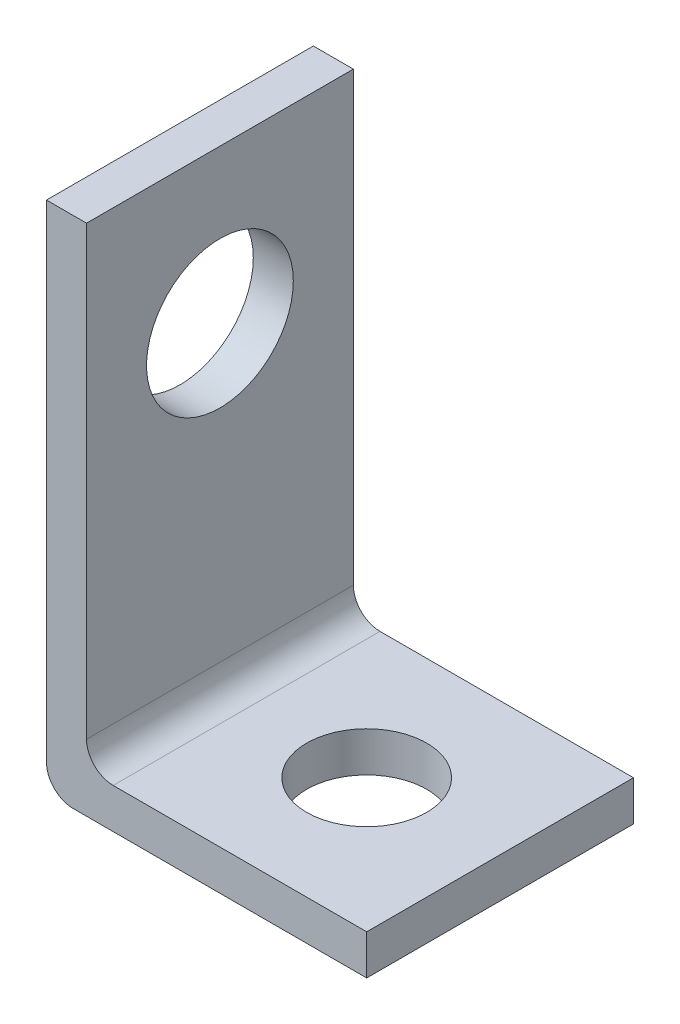
SolidWorks part; units mm, degrees
ref_plane "Plan de face" through (0, 0, 0) normal (0, 0, 1) x (1, 0, 0)
ref_plane "Plan de dessus" through (0, 0, 0) normal (0, 1, 0) x (1, 0, 0)
ref_plane "Plan de droite" through (0, 0, 0) normal (1, 0, 0) x (0, 0, -1)
sketch "Esquisse1" plane through (0, 0, 0) normal (0, 0, 1) x (1, 0, 0)
  line L0 (0, 0) -> (10.5, 0)
  line L1 (10.5, 0) -> (10.5, -1.5)
  line L2 (10.5, -1.5) -> (-1.5, -1.5)
  line L3 (-1.5, -1.5) -> (-1.5, 17.75)
  line L4 (-1.5, 17.75) -> (0, 17.75)
  line L5 (0, 17.75) -> (0, 0)
  dimension "D1" = 17.75
  dimension "D2" = 1.5
  dimension "D3" = 12
extrude "Boss.-Extru.1" add sketch "Esquisse1" along normal mid plane 10
fillet "Congé1" radius 1 2 edges at (-1.5, -1.5, 0) (0, 0, 0)
hole_wizard "Diamètre du perçage Ø5.5 (5.5)1" positions "Esquisse3" profile "Esquisse2" hole size "Ø5.5" standard "Ansi Metric" end condition through all
sketch "Esquisse3" plane through (0, 0, 0) normal (1, 0, 0) x (0, 0, -1)
  line L0 (0, 12) -> (0, 0)
  point P0 (0, 12)
  dimension "D1" = 12
sketch "Esquisse2" plane through (0, 12, 0) normal (0, 1, 0) x (0, 0, -1)
  line L0 (0, 0) -> (0, 1.5)
  line L1 (0, 1.5) -> (2.75, 1.5)
  line L2 (2.75, 1.5) -> (2.75, 0)
  line L5 (2.75, 0) -> (0, 0)
  line L11 (0, -6.35) -> (0, 107.95) construction
  dimension "Diamètre du perçage jusqu'au prochain" = 5.5
  dimension "Profondeur du perçage jusqu'au prochain" = 1.5
hole_wizard "Dégagement M41" positions "Esquisse5" profile "Esquisse4" hole size "M4" standard "Ansi Metric" end condition through all
sketch "Esquisse5" plane through (0, 0, 0) normal (0, 1, 0) x (1, 0, 0)
  line L0 (5.5, 0) -> (0, 0)
  line L2 (-1.5, 5) -> (-1.5, -5) construction
  point P0 (5.5, 0)
  dimension "D1" = 7
sketch "Esquisse4" plane through (5.5, 0, 0) normal (1, 0, 0) x (0, 0, 1)
  line L0 (0, 0) -> (0, 1.5)
  line L1 (0, 1.5) -> (2.25, 1.5)
  line L2 (2.25, 1.5) -> (2.25, 0)
  line L5 (2.25, 0) -> (0, 0)
  line L11 (0, -6.35) -> (0, 107.95) construction
  dimension "Diamètre du perçage jusqu'au prochain" = 4.5
  dimension "Profondeur du perçage jusqu'au prochain" = 1.5
